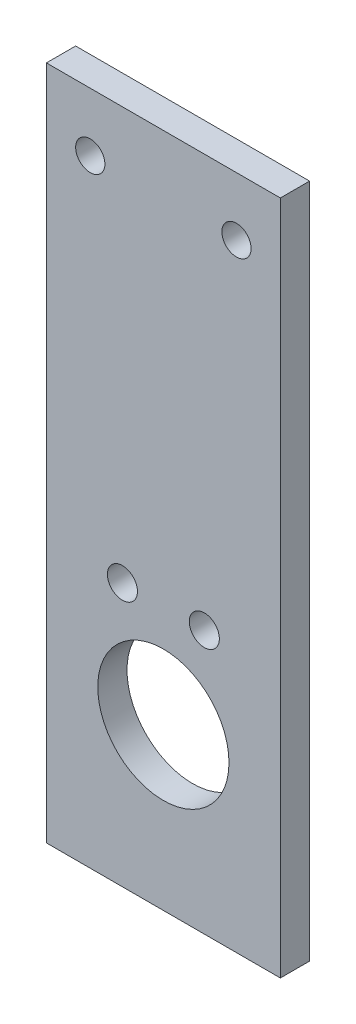
SolidWorks part; units mm, degrees
material "6061-T6 (SS)"
ref_plane "Front Plane" through (0, 0, 0) normal (0, 0, 1) x (1, 0, 0)
ref_plane "Top Plane" through (0, 0, 0) normal (0, 1, 0) x (1, 0, 0)
ref_plane "Right Plane" through (0, 0, 0) normal (1, 0, 0) x (0, 0, -1)
sketch "Sketch1" plane through (0, 0, 0) normal (0, 0, 1) x (1, 0, 0)
  line L0 (-25.4, -146.685) -> (25.4, -146.685)
  line L1 (-25.4, 0) -> (25.4, 0)
  line L2 (-25.4, 0) -> (-25.4, -146.685)
  line L4 (25.4, 0) -> (25.4, -146.685)
  circle A1 centre (0, -130.81) radius 14.2494 construction
  circle A2 centre (0, -111.76) radius 14.2494
  circle A3 centre (0, -92.71) radius 14.2494 construction
  circle A4 centre (0, -73.66) radius 14.2494 construction
  circle A5 centre (-15.875, -12.7) radius 3.175
  circle A6 centre (15.875, -12.7) radius 3.175
  circle A7 centre (0, -48.26) radius 14.2494 construction
  point P18 (0, 0)
  dimension "D6" = 28.4988
  dimension "D7" = 6.35
  dimension "D8" = 25.4
  dimension "D11" = 111.76
  dimension "D16" = 9.525
  dimension "D1" = 50.8
  dimension "D3" = 15.875
  dimension "D4" = 25.4
  dimension "D9" = 19.05
  dimension "D10" = 19.05
  dimension "D12" = 19.05
  dimension "D15" = 9.525
  dimension "D17" = 12.7
  dimension "D18" = 12.7
  dimension "D19" = 25.4
  dimension "D20" = 25.4
  dimension "D21" = 25.4
extrude "Boss-Extrude3" add sketch "Sketch1" along normal blind 6.35
chamfer "Chamfer1" [suppressed] distance 4.0894 angle 41
chamfer "Chamfer2" [suppressed] distance 4.0894 angle 41
sketch "Sketch2" plane through (0, 0, 6.35) normal (0, 0, 1) x (1, 0, 0)
  circle A0 centre (8.89, -89.535) radius 3.2639
  circle A1 centre (-8.89, -89.535) radius 3.2639
extrude "Cut-Extrude1" cut sketch "Sketch2" against normal through all
